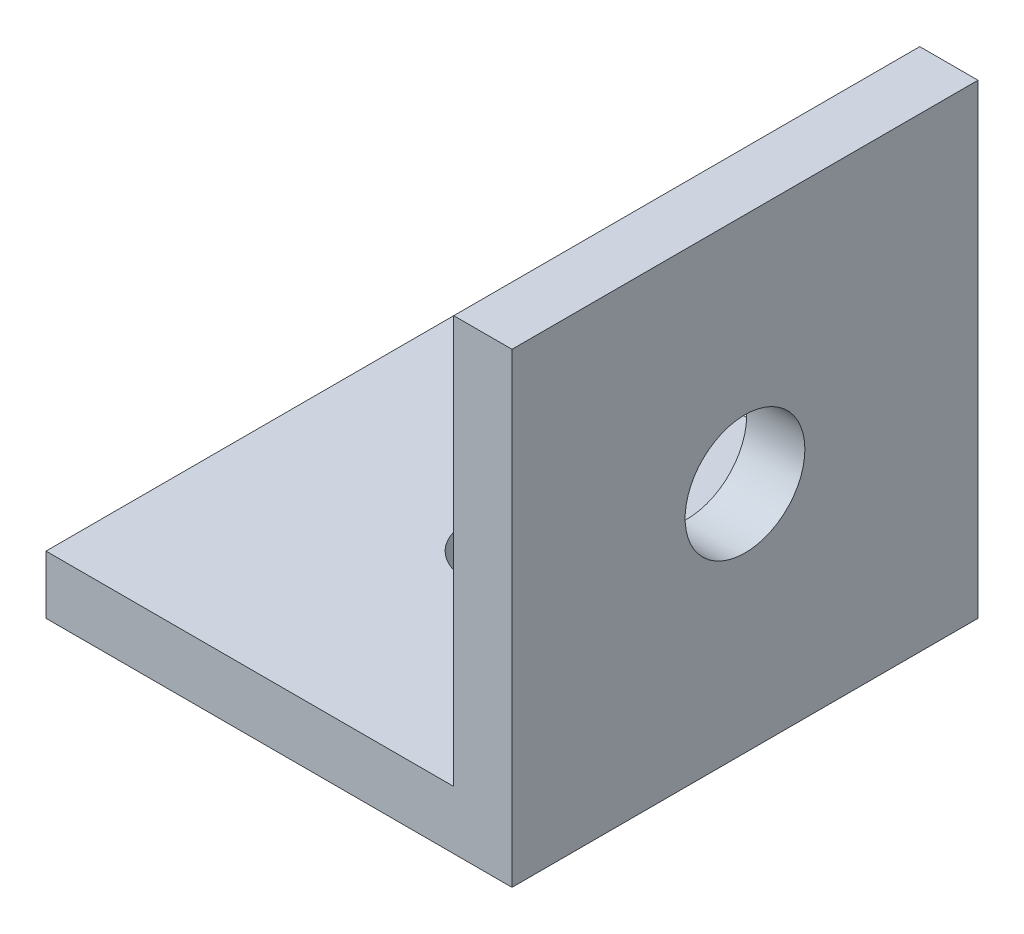
SolidWorks part; units mm, degrees
ref_plane "Front Plane" through (0, 0, 0) normal (0, 0, 1) x (1, 0, 0)
ref_plane "Top Plane" through (0, 0, 0) normal (0, 1, 0) x (1, 0, 0)
ref_plane "Right Plane" through (0, 0, 0) normal (1, 0, 0) x (0, 0, -1)
sketch "Sketch1" plane through (0, 0, 0) normal (0, 0, 1) x (1, 0, 0)
  line L0 (0, 3.175) -> (22.225, 3.175)
  line L1 (0, 0) -> (25.4, 0)
  line L2 (25.4, 0) -> (25.4, 25.4)
  line L3 (22.225, 3.175) -> (22.225, 25.4)
  line L4 (25.4, 25.4) -> (22.225, 25.4)
  line L5 (0, 3.175) -> (0, 0)
  dimension "D1" = 3.175
  dimension "D2" = 25.4
  dimension "D3" = 25.4
extrude "Boss-Extrude1" add sketch "Sketch1" along normal blind 25.4
hole_wizard "13/64 (0.20313) Diameter Hole1" positions "Sketch3" profile "Sketch2" hole size "13/64" standard "ANSI Inch" end condition through all
sketch "Sketch3" plane through (0, 0, 0) normal (0, -1, 0) x (-1, 0, 0)
  line L0 (0, 0) -> (-25.4, 0) construction
  line L1 (0, -25.4) -> (0, 0) construction
  point P0 (-12.7, -12.7)
  dimension "D1" = 12.7
  dimension "D2" = 12.7
sketch "Sketch2" plane through (12.7, 0, 12.7) normal (1, 0, 0) x (0, 0, -1)
  line L0 (0, 0) -> (0, 25.4)
  line L1 (0, 25.4) -> (2.5797, 25.4)
  line L2 (2.5797, 25.4) -> (2.5797, 0)
  line L5 (2.5797, 0) -> (0, 0)
  line L11 (0, -6.35) -> (0, 107.95) construction
  dimension "Thru Hole Dia." = 5.1594
  dimension "Thru Hole Depth" = 25.4
hole_wizard "F (0.257) Diameter Hole1" positions "Sketch5" profile "Sketch4" hole size "F" standard "ANSI Inch" end condition through all
sketch "Sketch5" plane through (25.4, 0, 0) normal (1, 0, 0) x (0, 0, -1)
  line L0 (-25.4, 0) -> (-25.4, 25.4) construction
  line L1 (-25.4, 25.4) -> (0, 25.4) construction
  point P0 (-12.7, 12.7)
  point P9 (-10.4063, 25.4)
  dimension "D1" = 12.7
  dimension "D2" = 12.7
sketch "Sketch4" plane through (25.4, 12.7, 12.7) normal (0, 1, 0) x (0, 0, -1)
  line L0 (0, 0) -> (0, 25.4)
  line L1 (0, 25.4) -> (3.2639, 25.4)
  line L2 (3.2639, 25.4) -> (3.2639, 0)
  line L5 (3.2639, 0) -> (0, 0)
  line L11 (0, -6.35) -> (0, 107.95) construction
  dimension "Thru Hole Dia." = 6.5278
  dimension "Thru Hole Depth" = 25.4
